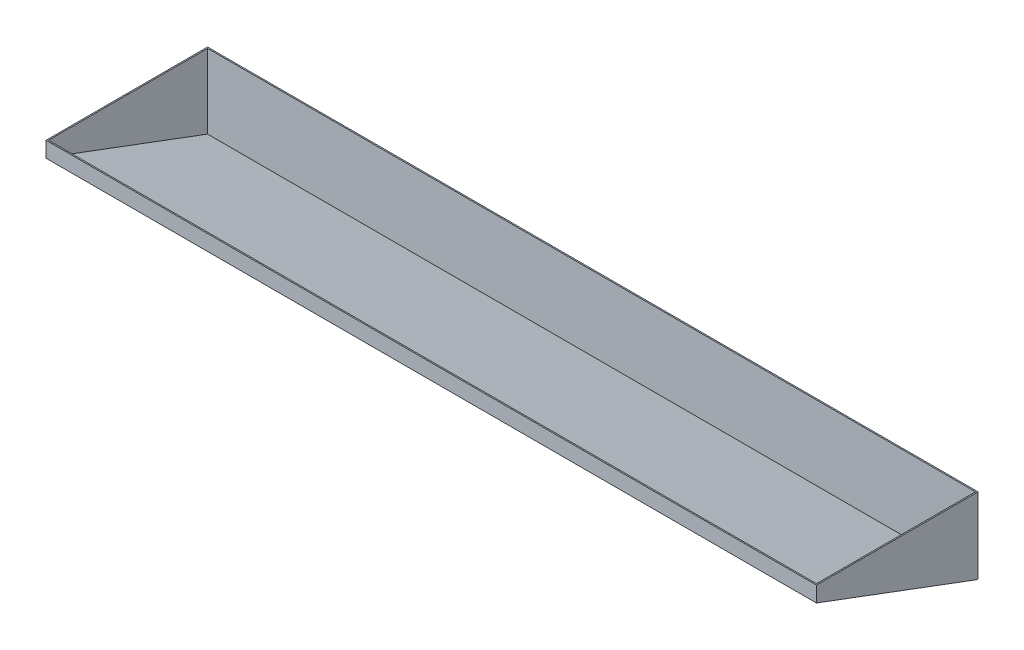
SolidWorks part; units mm, degrees
ref_plane "Front Plane" through (0, 0, 0) normal (0, 0, 1) x (1, 0, 0)
ref_plane "Top Plane" through (0, 0, 0) normal (0, 1, 0) x (1, 0, 0)
ref_plane "Right Plane" through (0, 0, 0) normal (1, 0, 0) x (0, 0, -1)
sketch "Sketch1" plane through (0, 0, 0) normal (0, 0, 1) x (1, 0, 0)
  line L1 (0, 0) -> (510, 0)
  line L2 (0, 0) -> (0, 50)
  line L3 (0, 50) -> (510, 50)
  line L4 (510, 0) -> (510, 50)
extrude "Boss-Extrude1" add sketch "Sketch1" along normal blind 0.8
sketch3d "3DSketch1"
  line L3 (0, 50, 0.8) -> (0, 0, 0.8)
  line L7 (0, 50, 0.8) -> (0, 0, 0.8)
  line L8 (0, 0, 0.8) -> (510, 0, 0.8)
  line L9 (510, 0, 0.8) -> (510, 50, 0.8)
  line L10 (510, 50, 0.8) -> (0, 50, 0.8)
  line L12 (0, 0, 0.8) -> (510, 0, 0.8)
  line L13 (510, 0, 0.8) -> (510, 50, 0.8)
  line L14 (510, 50, 0.8) -> (0, 50, 0.8)
  dimension "D1" = 0
ref_plane "Plane1" through (0, 0, 0) normal (-1, 0, 0) x (0, 0, 1)
sketch "Sketch3" plane through (0, 0, 0) normal (-1, 0, 0) x (0, 0, 1)
  line L0 (0.8, 0) -> (106.9488, 39.7154)
  line L1 (106.9488, 39.7154) -> (106.9488, 50)
  line L2 (0.8, 50) -> (74.5066, 50)
  line L3 (0.8, 50) -> (0.8, 0)
  line L5 (89.6012, 50) -> (74.5066, 50)
  line L6 (106.9488, 50) -> (90.0528, 50)
  line L7 (90.0528, 50) -> (89.6012, 50)
extrude "Boss-Extrude2" add sketch "Sketch3" against normal blind 510
shell "Shell3" thickness 0.8
